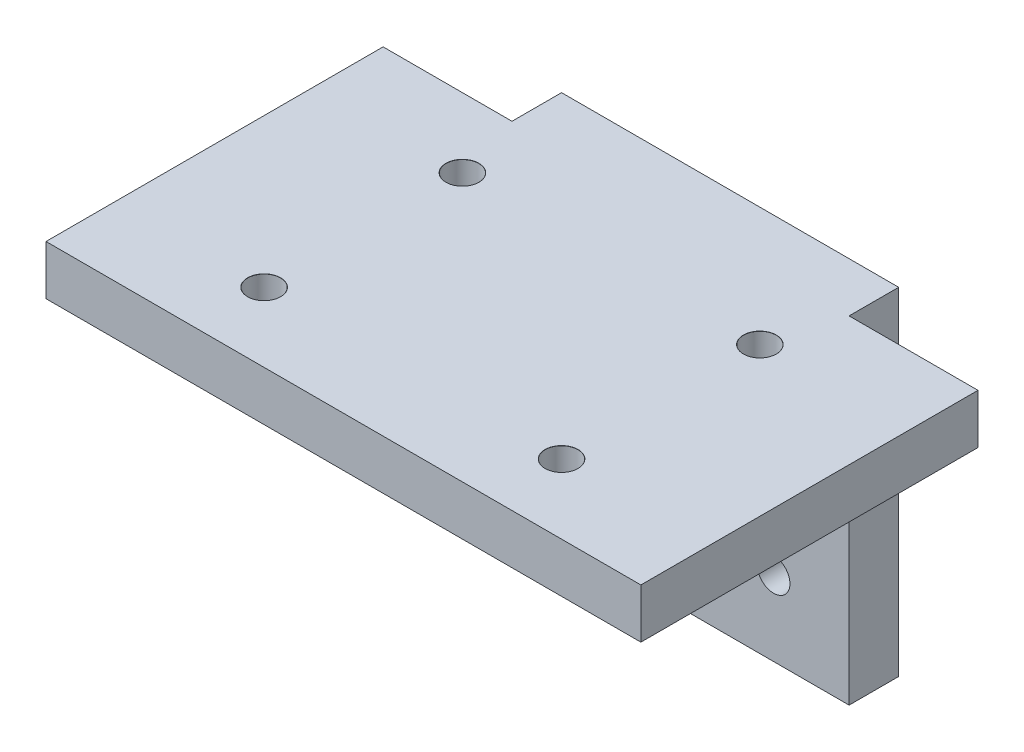
SolidWorks part; units mm, degrees
ref_plane "Front Plane" through (0, 0, 0) normal (0, 0, 1) x (1, 0, 0)
ref_plane "Top Plane" through (0, 0, 0) normal (0, 1, 0) x (1, 0, 0)
ref_plane "Right Plane" through (0, 0, 0) normal (1, 0, 0) x (0, 0, -1)
sketch "Sketch1" plane through (0, 0, 0) normal (0, 0, 1) x (1, 0, 0)
  line L2 (-34, 34) -> (34, 34)
  line L3 (34, 34) -> (34, -34)
  line L7 (-34, 34) -> (-34, -34)
  line L10 (-34, -34) -> (34, -34)
  circle A1 centre (0, 0) radius 14.29
  point P2 (0, 0)
  point P3 (0, -34)
  point P4 (-34, 0)
  point P10 (0, 0)
  dimension "D1" = 28.58
  dimension "D2" = 68
  dimension "D3" = 68
extrude "Boss-Extrude1" add sketch "Sketch1" along normal blind 10
hole_wizard "M6 Clearance Hole1" positions "Sketch2" profile "Sketch3" hole size "M6" standard "ANSI Metric" end condition up to next
sketch "Sketch2" plane through (0, 0, 0) normal (0, 0, -1) x (-1, 0, 0)
  line L0 (-18.7687, 18.7687) -> (18.7687, 18.7687) construction
  line L2 (18.7687, 18.7687) -> (18.7687, -18.7687) construction
  line L4 (-18.7687, 18.7687) -> (18.7687, -18.7687) construction
  line L5 (0, 0) -> (18.7687, 18.7687) construction
  point P0 (-18.7687, 18.7687)
  point P2 (18.7687, 18.7687)
  point P4 (-18.7687, -18.7687)
  point P6 (18.7687, -18.7687)
  point P18 (0, 18.7687)
  point P25 (0, 0)
  dimension "D1" = 53.086
sketch "Sketch3" plane through (18.7687, 18.7687, 0) normal (1, 0, 0) x (0, 1, 0)
  line L0 (0, 0) -> (0, 10)
  line L1 (0, 10) -> (3.3, 10)
  line L2 (3.3, 10) -> (3.3, 0.021)
  line L3 (3.3, 0.021) -> (3.325, 0)
  line L5 (3.325, 0) -> (0, 0)
  line L6 (-3.3, 0.021) -> (-3.325, 0) construction
  line L11 (0, -6.35) -> (0, 107.95) construction
  dimension "Thru Hole Dia." = 6.6
  dimension "Thru Hole Depth" = 10
  dimension "Near C'Sink Dia." = 6.65
  dimension "Near C'Sink Angle" = 100
sketch "Sketch5" plane through (0, 0, 10) normal (0, 0, 1) x (1, 0, 0)
  line L0 (34, -34) -> (34, 34) construction
  line L1 (-60, 34) -> (60, 34)
  line L2 (-60, 34) -> (-60, 24)
  line L3 (-60, 24) -> (60, 24)
  line L4 (60, 34) -> (60, 24)
  point P7 (0, 24)
  dimension "D1" = 10
  dimension "D2" = 120
extrude "Boss-Extrude3" add sketch "Sketch5" along normal blind 68
hole_wizard "M6 Clearance Hole2" positions "Sketch6" profile "Sketch7" hole size "M6" standard "ANSI Metric" end condition up to next
sketch "Sketch6" plane through (0, 34, 0) normal (0, 1, 0) x (1, 0, 0)
  line L0 (-30, -24) -> (30, -24) construction
  line L1 (30, -24) -> (30, -64) construction
  line L2 (-60, -78) -> (-60, -10) construction
  point P0 (-30, -24)
  point P2 (30, -24)
  point P4 (-30, -64)
  point P6 (30, -64)
  point P15 (0, 0)
  point P16 (0, 0)
  point P19 (0, -24)
  point P22 (-60, -44)
  point P23 (30, -44)
  dimension "D1" = 60
  dimension "D2" = 40
sketch "Sketch7" plane through (-30, 34, 24) normal (1, 0, 0) x (0, 0, 1)
  line L0 (0, 0) -> (0, 10)
  line L1 (0, 10) -> (3.3, 10)
  line L2 (3.3, 10) -> (3.3, 0.021)
  line L3 (3.3, 0.021) -> (3.325, 0)
  line L5 (3.325, 0) -> (0, 0)
  line L6 (-3.3, 0.021) -> (-3.325, 0) construction
  line L11 (0, -6.35) -> (0, 107.95) construction
  dimension "Thru Hole Dia." = 6.6
  dimension "Thru Hole Depth" = 10
  dimension "Near C'Sink Dia." = 6.65
  dimension "Near C'Sink Angle" = 100
